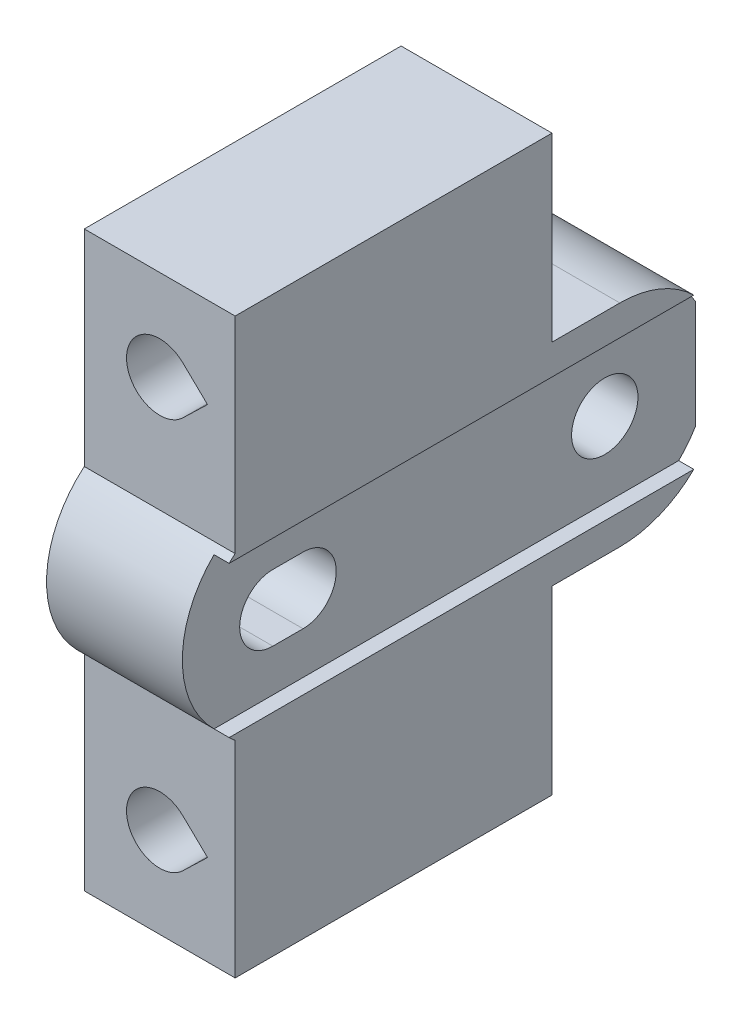
SolidWorks part; units mm, degrees
ref_plane "Front Plane" through (0, 0, 0) normal (0, 0, 1) x (1, 0, 0)
ref_plane "Top Plane" through (0, 0, 0) normal (0, 1, 0) x (1, 0, 0)
ref_plane "Right Plane" through (0, 0, 0) normal (1, 0, 0) x (0, 0, -1)
ref_plane "Plane1" through (4.9, 0, 0) normal (-1, 0, 0) x (0, -1, 0)
sketch "Sketch1" plane through (4.9, 0, 0) normal (-1, 0, 0) x (0, -1, 0)
  line L0 (7, -10.5) -> (7, 15)
  line L1 (7, 15) -> (5.3619, 15)
  line L2 (-5.3619, 15) -> (-7, 15)
  line L3 (-7, 15) -> (-7, -10.5)
  line L4 (-3.6056, -16.5) -> (3.6056, -16.5)
  arc A0 (5.3619, 15) -> (-5.3619, 15) centre (0, 10.5) ccw
  arc A1 (-7, -10.5) -> (-3.6056, -16.5) centre (0, -10.5) ccw
  arc A2 (3.6056, -16.5) -> (7, -10.5) centre (0, -10.5) ccw
extrude "Boss-Extrude1" add sketch "Sketch1" against normal blind 9
sketch "Sketch2" plane through (13.9, 0, 0) normal (1, 0, 0) x (0, 0, -1)
  line L0 (-15, -7) -> (-15, -5.3619)
  line L1 (-15.399, -5) -> (15.399, -5)
  line L2 (10.5, -7) -> (-15, -7)
  arc A0 (-15, -5.3619) -> (-15.399, -5) centre (-10.5, 0) cw
  arc A1 (15.399, -5) -> (10.5, -7) centre (10.5, 0) cw
extrude "Boss-Extrude2" add sketch "Sketch2" along normal blind 1
sketch "Sketch3" plane through (13.9, 0, 0) normal (1, 0, 0) x (0, 0, -1)
  line L0 (-15, 7) -> (10.5, 7)
  line L1 (15.399, 5) -> (-15.399, 5)
  line L2 (-15, 5.3619) -> (-15, 7)
  arc A0 (10.5, 7) -> (15.399, 5) centre (10.5, 0) cw
  arc A1 (-15.399, 5) -> (-15, 5.3619) centre (-10.5, 0) cw
extrude "Boss-Extrude3" add sketch "Sketch3" along normal blind 1
sketch "Sketch4" plane through (0, -7, 0) normal (0, -1, 0) x (1, 0, 0)
  line L0 (14.9, 15) -> (14.9, -6)
  line L1 (14.9, -6) -> (4.9, -6)
  line L2 (4.9, -6) -> (4.9, 15)
  line L3 (4.9, 15) -> (14.9, 15)
extrude "Boss-Extrude4" add sketch "Sketch4" along normal blind 12
sketch "Sketch5" plane through (0, 7, 0) normal (0, 1, 0) x (-1, 0, 0)
  line L0 (-14.9, -6) -> (-14.9, 15)
  line L1 (-14.9, 15) -> (-4.9, 15)
  line L2 (-4.9, 15) -> (-4.9, -6)
  line L3 (-4.9, -6) -> (-14.9, -6)
extrude "Boss-Extrude5" add sketch "Sketch5" along normal blind 12
sketch "Sketch6" plane through (0, 0, -6) normal (0, 0, -1) x (-1, 0, 0)
  line L0 (-11.4282, 14.5825) -> (-13.067, 13)
  line L1 (-13.067, 13) -> (-11.4282, 11.4175)
  arc A0 (-11.4282, 11.4175) -> (-11.4282, 14.5825) centre (-9.9, 13) ccw
extrude "Cut-Extrude1" cut sketch "Sketch6" against normal through all
sketch "Sketch7" plane through (4.9, 0, 0) normal (-1, 0, 0) x (0, 0, 1)
  line L0 (9.5, -2.2) -> (11.5, -2.2)
  line L1 (11.5, 2.2) -> (9.5, 2.2)
  arc A0 (11.5, -2.2) -> (11.5, 2.2) centre (11.5, 0) ccw
  arc A1 (9.5, 2.2) -> (9.5, -2.2) centre (9.5, 0) ccw
extrude "Cut-Extrude2" cut sketch "Sketch7" against normal through all
sketch "Sketch8" plane through (0, 0, -6) normal (0, 0, -1) x (-1, 0, 0)
  line L0 (-11.4282, -11.4175) -> (-13.067, -13)
  line L1 (-13.067, -13) -> (-11.4282, -14.5825)
  arc A0 (-11.4282, -14.5825) -> (-11.4282, -11.4175) centre (-9.9, -13) ccw
extrude "Cut-Extrude3" cut sketch "Sketch8" against normal through all
hole_wizard "Hole1" positions "Sketch10" profile "Sketch9" legacy
sketch "Sketch10" plane through (13.9, 0, 0) normal (1, 0, 0) x (0, 0, -1)
  point P0 (10.5, 0)
sketch "Sketch9" plane through (13.9, 0, -10.5) normal (0, 1, 0) x (0, 0, -1)
  line L0 (0, 0) -> (0, 9)
  line L1 (0, 9) -> (2.2, 9)
  line L2 (2.2, 9) -> (2.2, 0)
  line L3 (2.2, 0) -> (0, 0)
  line L4 (0, 110) -> (0, -10) construction
  dimension "Diameter" = 4.4
  dimension "Depth" = 9
